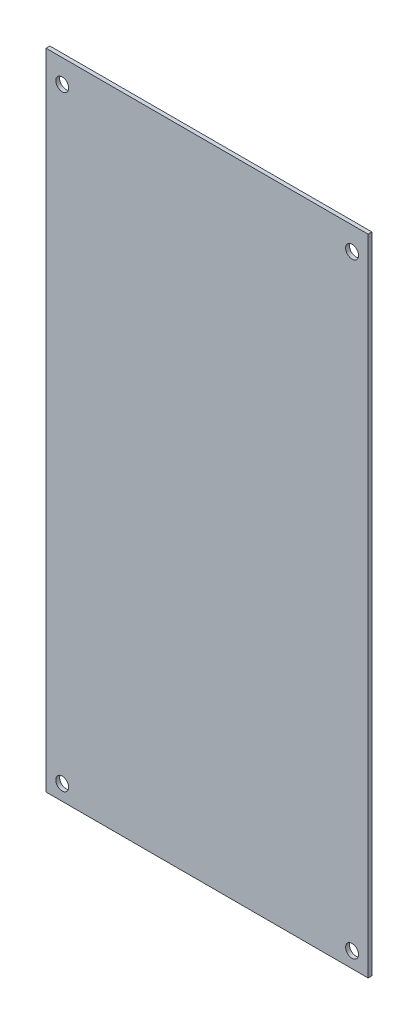
SolidWorks part; units mm, degrees
ref_plane "Plan de face" through (0, 0, 0) normal (0, 0, 1) x (1, 0, 0)
ref_plane "Plan de dessus" through (0, 0, 0) normal (0, 1, 0) x (1, 0, 0)
ref_plane "Plan de droite" through (0, 0, 0) normal (1, 0, 0) x (0, 0, -1)
sketch "Esquisse1" plane through (0, 0, 0) normal (0, 0, 1) x (1, 0, 0)
  line L0 (0, 0) -> (250, 0)
  line L1 (0, 0) -> (0, 500)
  line L2 (250, 0) -> (250, 500)
  line L3 (0, 500) -> (250, 500)
  dimension "D1" = 250
  dimension "D2" = 500
extrude "Boss.-Extru.1" add sketch "Esquisse1" along normal blind 3
sketch "Esquisse2" plane through (0, 0, 3) normal (0, 0, 1) x (1, 0, 0)
  circle A0 centre (12.5619, 11.9938) radius 5
extrude "Enlèv. mat.-Extru.1" cut sketch "Esquisse2" against normal up to next contours A0
pattern_linear "Répétition linéaire1" count 2 spacing 225 along (1, 0, 0) of "Enlèv. mat.-Extru.1"
pattern_linear "Répétition linéaire2" count 2 spacing 470 along (0, 1, 0) of "Répétition linéaire1", "Enlèv. mat.-Extru.1"
